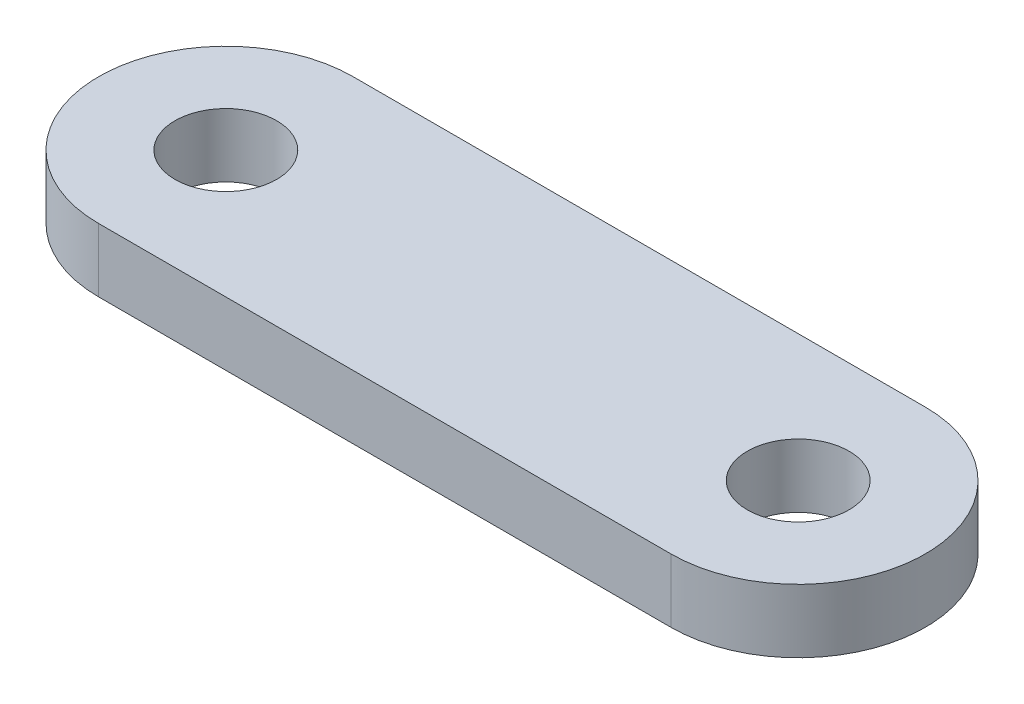
SolidWorks part; units mm, degrees
material "1060 Сплав"
ref_plane "Спереди" through (0, 0, 0) normal (0, 0, 1) x (1, 0, 0)
ref_plane "Сверху" through (0, 0, 0) normal (0, 1, 0) x (1, 0, 0)
ref_plane "Справа" through (0, 0, 0) normal (1, 0, 0) x (0, 0, -1)
sketch "Эскиз1" plane through (0, 0, 0) normal (0, 1, 0) x (1, 0, 0)
  line L1 (0, 0) -> (18, 0)
  line L3 (0, -8) -> (18, -8)
  arc A0 (0, 0) -> (0, -8) centre (0, -4) ccw
  arc A1 (18, 0) -> (18, -8) centre (18, -4) cw
  circle A2 centre (0, -4) radius 1.6
  circle A3 centre (18, -4) radius 1.6
  dimension "D1" = 18
  dimension "D2" = 8
extrude "Бобышка-Вытянуть1" add sketch "Эскиз1" along normal blind 2
